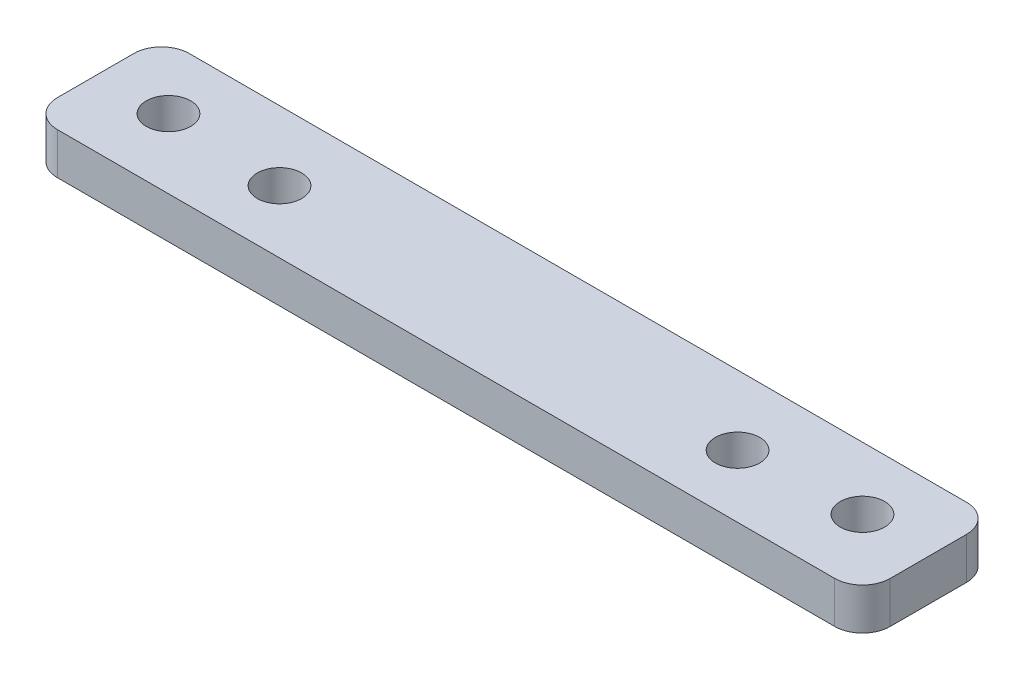
SolidWorks part; units mm, degrees
ref_plane "前视基准面" through (0, 0, 0) normal (0, 0, 1) x (1, 0, 0)
ref_plane "上视基准面" through (0, 0, 0) normal (0, 1, 0) x (1, 0, 0)
ref_plane "右视基准面" through (0, 0, 0) normal (1, 0, 0) x (0, 0, -1)
sketch "草图1" plane through (0, 0, 0) normal (0, 1, 0) x (1, 0, 0)
  line L1 (30, -4.75) -> (-30, -4.75)
  line L2 (30, -4.75) -> (30, 4.75)
  line L3 (30, 4.75) -> (-30, 4.75)
  line L4 (-30, -4.75) -> (-30, 4.75)
  line L5 (30, -4.75) -> (-30, 4.75) construction
  line L6 (30, 4.75) -> (-30, -4.75) construction
  point P0 (0, 0)
  dimension "D1" = 60
  dimension "D2" = 9.5
extrude "凸台-拉伸1" add sketch "草图1" along normal blind 3
sketch "草图2" plane through (0, 3, 0) normal (0, 1, 0) x (1, 0, 0)
  line L0 (-30, 0) -> (0, 0) construction
  line L1 (-30, 4.75) -> (-30, -4.75) construction
  line L2 (0, 0) -> (0, 4.75) construction
  line L3 (30, 4.75) -> (-30, 4.75) construction
  circle A0 centre (-16.5, -0.25) radius 1.6
  circle A1 centre (-25, 0.25) radius 1.6
  circle A2 centre (25, 0.25) radius 1.6
  circle A3 centre (16.5, -0.25) radius 1.6
  dimension "D1" = 3.2
  dimension "D2" = 3.2
  dimension "D3" = 33
  dimension "D4" = 50
  dimension "D5" = 5
  dimension "D6" = 4.5
extrude "切除-拉伸1" cut sketch "草图2" against normal blind 3
fillet "圆角1" radius 2 4 edges at (-30, 1.5, -4.75) (30, 1.5, -4.75) (30, 1.5, 4.75) (-30, 1.5, 4.75)
